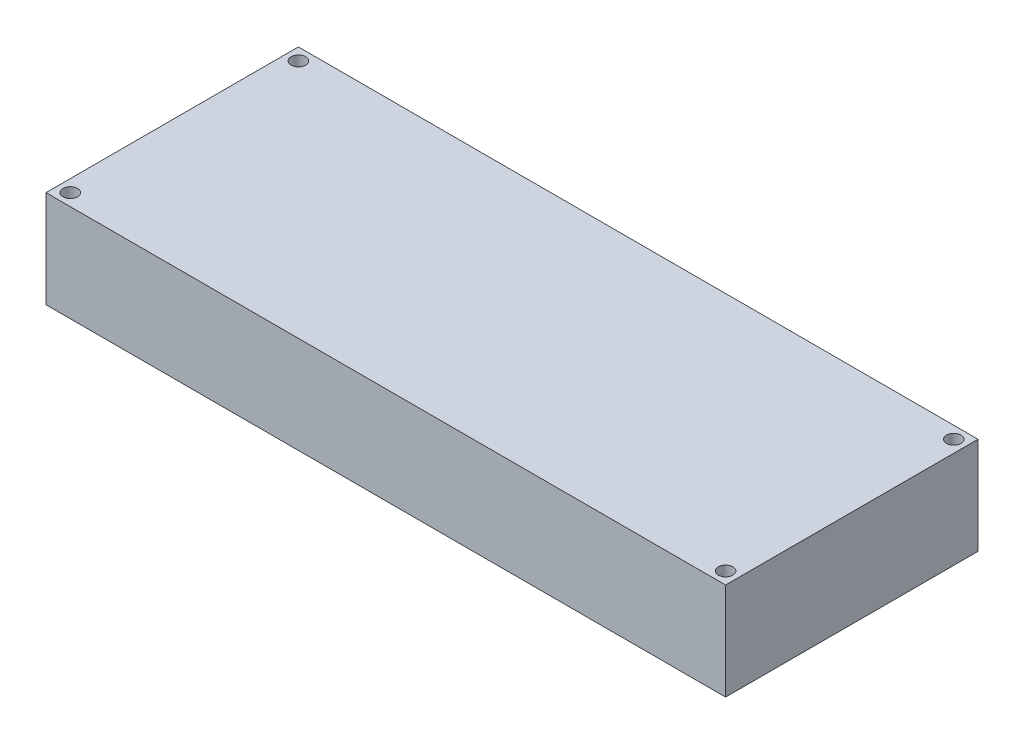
SolidWorks part; units mm, degrees
ref_plane "Płaszczyzna przednia" through (0, 0, 0) normal (0, 0, 1) x (1, 0, 0)
ref_plane "Płaszczyzna górna" through (0, 0, 0) normal (0, 1, 0) x (1, 0, 0)
ref_plane "Płaszczyzna prawa" through (0, 0, 0) normal (1, 0, 0) x (0, 0, -1)
sketch "Szkic1" plane through (0, 0, 0) normal (0, 1, 0) x (1, 0, 0)
  line L1 (0, 0) -> (140, 0)
  line L2 (0, 0) -> (0, 52)
  line L3 (0, 52) -> (140, 52)
  line L4 (140, 0) -> (140, 52)
  line L5 (70, 0) -> (137.0423, 0)
  circle A3 centre (2.5, 49.5) radius 1.5
  circle A4 centre (2.5, 2.5) radius 1.5
  circle A5 centre (137.5, 2.5) radius 1.5
  circle A6 centre (137.5, 49.5) radius 1.5
  dimension "D1" = 140
  dimension "D3" = 3
  dimension "D4" = 2.5
  dimension "D2" = 52
extrude "Dodanie-wyciągnięcie1" add sketch "Szkic1" along normal blind 20
